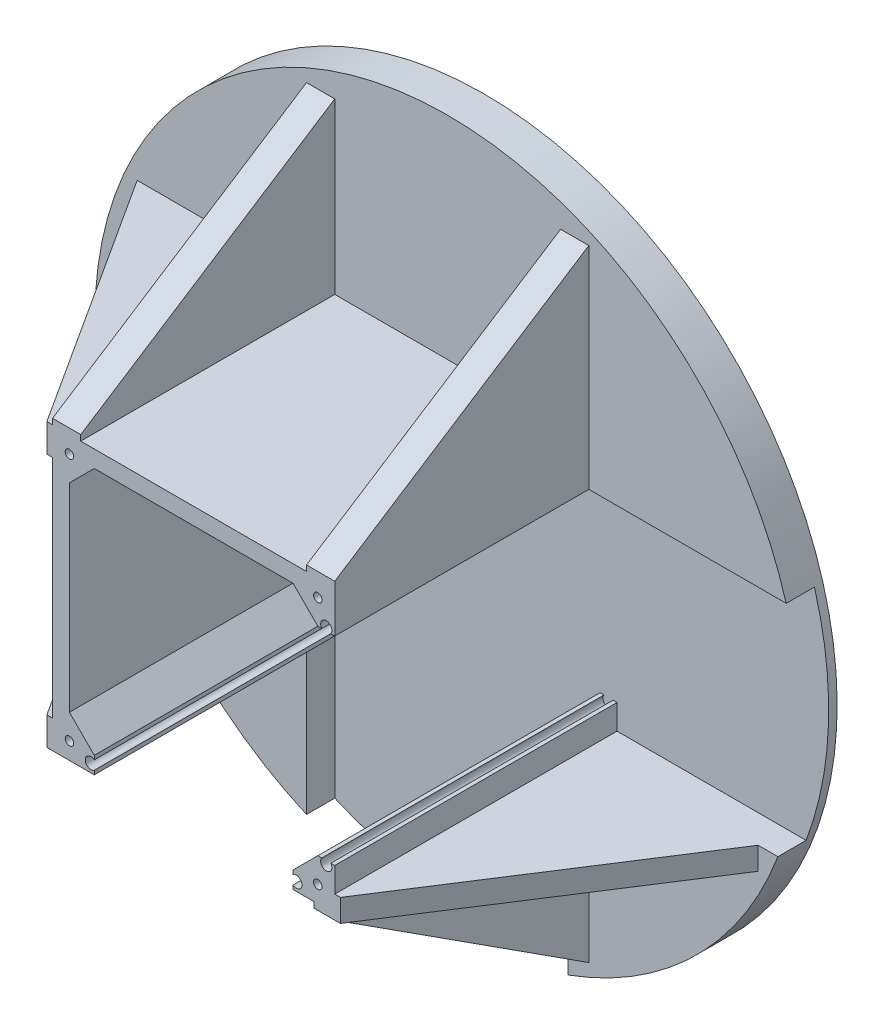
SolidWorks part; units mm, degrees
ref_plane "前视基准面" through (0, 0, 0) normal (0, 0, 1) x (1, 0, 0)
ref_plane "上视基准面" through (0, 0, 0) normal (0, 1, 0) x (1, 0, 0)
ref_plane "右视基准面" through (0, 0, 0) normal (1, 0, 0) x (0, 0, -1)
sketch "草图1" plane through (0, 0, 0) normal (0, 0, 1) x (1, 0, 0)
  line L0 (-3, -3.1574) -> (-3, -40.8426)
  line L1 (4.4, 0) -> (39.6, 0)
  line L2 (0, -4.4) -> (0, -39.6)
  line L3 (4.4, -44) -> (39.6, -44)
  line L4 (44, -4.4) -> (44, -39.6)
  line L5 (44, -44) -> (0, 0) construction
  line L6 (39.6, -44) -> (44, -39.6)
  line L7 (44, 0) -> (0, -44) construction
  line L8 (0, -4.4) -> (4.4, 0)
  line L9 (0, -22) -> (48.6163, -22) construction
  line L10 (39.6, 0) -> (44, -4.4)
  line L11 (0, -39.6) -> (4.4, -44)
  line L12 (-3, -40.8426) -> (3.1574, -47)
  line L13 (3.1574, -47) -> (40.8426, -47)
  line L14 (40.8426, -47) -> (47, -40.8426)
  line L15 (47, -3.1574) -> (47, -40.8426)
  line L16 (40.8426, 3) -> (47, -3.1574)
  line L17 (3.1574, 3) -> (40.8426, 3)
  line L18 (-3, -3.1574) -> (3.1574, 3)
  line L19 (-3, -40.8426) -> (-3, -47)
  line L20 (-3, -47) -> (3.1574, -47)
  line L21 (47, -40.8426) -> (47, -47)
  line L22 (47, -47) -> (40.8426, -47)
  dimension "D1" = 44
  dimension "D2" = 44
  dimension "D3" = 4.4
  dimension "D4" = 4.4
  dimension "D5" = 35.2
  dimension "D6" = 6.2225
  dimension "D7" = 35.2
  dimension "D8" = 35.2
  dimension "D9" = 3
extrude "凸台-拉伸2" add sketch "草图1" along normal blind 50 contours L19 L20 L12 | L18 L0 L12 L13 L14 L15 L16 L17 L11 L2 L8 L1 L10 L4 L6 L3 | L22 L21 L14
sketch "草图2" plane through (0, 0, 50) normal (0, 0, 1) x (1, 0, 0)
  line L0 (4.4, -44) -> (4.4, -47)
  line L1 (7.0436, -44) -> (7.0436, -44.7) construction
  line L2 (4.4, -44) -> (39.6, -44) construction
  line L3 (7.0436, -47) -> (7.0436, -46.3) construction
  line L4 (7.0881, -44.7) -> (4.4, -44.7) construction
  line L5 (7.0436, -46.3) -> (4.4, -46.3) construction
  line L6 (-3, -3.1574) -> (-3, -47)
  line L7 (-3, -47) -> (47, -47)
  line L8 (47, -47) -> (47, -3.1574)
  line L9 (47, -3.1574) -> (40.8426, 3)
  line L10 (40.8426, 3) -> (3.1574, 3)
  line L11 (3.1574, 3) -> (-3, -3.1574)
  line L12 (-3, -3.1574) -> (-3, -47)
  line L13 (-3, -47) -> (47, -47)
  line L14 (47, -47) -> (47, -3.1574)
  line L15 (47, -3.1574) -> (40.8426, 3)
  line L16 (40.8426, 3) -> (3.1574, 3)
  line L17 (3.1574, 3) -> (-3, -3.1574)
  line L18 (22, -47) -> (22, -44) construction
  line L19 (39.6, -44) -> (39.6, -47)
  circle A0 centre (3.8, -45.5) radius 1
  circle A1 centre (40.2, -45.5) radius 1
  line M13 (-3, -47) -> (47, -47)
  line M25 (39.6, -44) -> (4.4, -44)
  dimension "D4" = 2
  dimension "D2" = 0.7
  dimension "D3" = 0.7
  dimension "D1" = 0
extrude "切除-拉伸1" cut sketch "草图2" against normal blind 52 contours L0 A0 | L0 A0 | L19 A1 L0 A0 M25 M13 | A1 L19 | A1 L19
sketch "草图3" plane through (0, 0, 0) normal (0, 0, -1) x (-1, 0, 0)
  line L0 (0, -22) -> (-44, -22) construction
  line L1 (0, -4.4) -> (0, -39.6) construction
  line L2 (-44, -4.4) -> (-44, -39.6) construction
  line L3 (-22, 0) -> (-22, -65.109) construction
  line L4 (-4.4, 0) -> (-39.6, 0) construction
  line L5 (-4.4, -47) -> (-39.6, -47)
  line L23 (-39.6, -44) -> (-44, -39.6)
  line L24 (-39.6, -44.7) -> (-39.6, -44)
  line L25 (-39.6, -47) -> (-39.6, -46.3)
  line L26 (-47, -47) -> (-39.6, -47)
  line L27 (-47, -3.1574) -> (-47, -47)
  line L28 (-40.8426, 3) -> (-47, -3.1574)
  line L29 (-3.1574, 3) -> (-40.8426, 3)
  line L30 (3, -3.1574) -> (-3.1574, 3)
  line L31 (3, -47) -> (3, -3.1574)
  line L32 (-4.4, -47) -> (3, -47)
  line L33 (-4.4, -46.3) -> (-4.4, -47)
  line L34 (-4.4, -44) -> (-4.4, -44.7)
  line L35 (0, -39.6) -> (-4.4, -44)
  line L36 (0, -4.4) -> (0, -39.6)
  line L37 (-4.4, 0) -> (0, -4.4)
  line L38 (-39.6, 0) -> (-4.4, 0)
  line L39 (-44, -4.4) -> (-39.6, 0)
  line L40 (-44, -39.6) -> (-44, -4.4)
  line L41 (-39.6, -44) -> (-44, -39.6)
  line L42 (-39.6, -44.7) -> (-39.6, -44)
  line L43 (-39.6, -47) -> (-39.6, -46.3)
  line L44 (-47, -47) -> (-39.6, -47)
  line L45 (-47, -3.1574) -> (-47, -47)
  line L46 (-40.8426, 3) -> (-47, -3.1574)
  line L47 (-3.1574, 3) -> (-40.8426, 3)
  line L48 (3, -3.1574) -> (-3.1574, 3)
  line L49 (3, -47) -> (3, -3.1574)
  line L50 (-4.4, -47) -> (3, -47)
  line L51 (-4.4, -46.3) -> (-4.4, -47)
  line L52 (-4.4, -44) -> (-4.4, -44.7)
  line L53 (0, -39.6) -> (-4.4, -44)
  line L54 (0, -4.4) -> (0, -39.6)
  line L55 (-4.4, 0) -> (0, -4.4)
  line L56 (-39.6, 0) -> (-4.4, 0)
  line L57 (-44, -4.4) -> (-39.6, 0)
  line L58 (-44, -39.6) -> (-44, -4.4)
  circle A0 centre (-22, -22) radius 62.5
  arc A2 (-39.6, -44.7) -> (-39.6, -46.3) centre (-40.2, -45.5) ccw
  arc A3 (-4.4, -46.3) -> (-4.4, -44.7) centre (-3.8, -45.5) ccw
  arc A4 (-39.6, -44.7) -> (-39.6, -46.3) centre (-40.2, -45.5) ccw
  arc A5 (-4.4, -46.3) -> (-4.4, -44.7) centre (-3.8, -45.5) ccw
  dimension "D2" = 125
  dimension "D1" = 0
extrude "凸台-拉伸3" add sketch "草图3" along normal blind 1.5 contours A0
sketch "草图4" plane through (0, 0, 0) normal (0, 0, 1) x (1, 0, 0)
  line L1 (-3, -47) -> (-3, -79.2822)
  line L2 (47, -44) -> (80.5, -44)
  line L3 (47, -4.4) -> (81.9707, -4.4)
  line L4 (43.3, -47) -> (43.3, -80.7585)
  line L18 (44, -39.6) -> (39.6, -44)
  line L19 (39.6, -44) -> (39.6, -44.7)
  line L20 (39.6, -46.3) -> (39.6, -47)
  line L21 (39.6, -47) -> (47, -47)
  line L22 (47, -47) -> (47, -3.1574)
  line L23 (47, -3.1574) -> (40.8426, 3)
  line L24 (40.8426, 3) -> (3.1574, 3)
  line L25 (3.1574, 3) -> (-3, -3.1574)
  line L26 (-3, -3.1574) -> (-3, -47)
  line L27 (-3, -47) -> (4.4, -47)
  line L28 (4.4, -47) -> (4.4, -46.3)
  line L29 (4.4, -44.7) -> (4.4, -44)
  line L30 (4.4, -44) -> (0, -39.6)
  line L31 (0, -39.6) -> (0, -4.4)
  line L32 (0, -4.4) -> (4.4, 0)
  line L33 (4.4, 0) -> (39.6, 0)
  line L34 (39.6, 0) -> (44, -4.4)
  line L35 (44, -4.4) -> (44, -39.6)
  line L36 (44, -39.6) -> (39.6, -44)
  line L37 (39.6, -44) -> (39.6, -44.7)
  line L38 (39.6, -46.3) -> (39.6, -47)
  line L39 (39.6, -47) -> (47, -47)
  line L40 (47, -47) -> (47, -3.1574)
  line L41 (47, -3.1574) -> (40.8426, 3)
  line L42 (40.8426, 3) -> (3.1574, 3)
  line L43 (3.1574, 3) -> (-3, -3.1574)
  line L44 (-3, -3.1574) -> (-3, -47)
  line L45 (-3, -47) -> (4.4, -47)
  line L46 (4.4, -47) -> (4.4, -46.3)
  line L47 (4.4, -44.7) -> (4.4, -44)
  line L48 (4.4, -44) -> (0, -39.6)
  line L49 (0, -39.6) -> (0, -4.4)
  line L50 (0, -4.4) -> (4.4, 0)
  line L51 (4.4, 0) -> (39.6, 0)
  line L52 (39.6, 0) -> (44, -4.4)
  line L53 (44, -4.4) -> (44, -39.6)
  circle A1 centre (22, -22) radius 62.5
  circle A2 centre (22, -22) radius 62.5
  arc A4 (39.6, -46.3) -> (39.6, -44.7) centre (40.2, -45.5) ccw
  arc A5 (4.4, -44.7) -> (4.4, -46.3) centre (3.8, -45.5) ccw
  arc A6 (39.6, -46.3) -> (39.6, -44.7) centre (40.2, -45.5) ccw
  arc A7 (4.4, -44.7) -> (4.4, -46.3) centre (3.8, -45.5) ccw
  circle M22 centre (22, -22) radius 62.5
  line M35 (-3, -47) -> (-3, -3.1574)
  line M36 (-3, -3.1574) -> (3.1574, 3)
  line M37 (3.1574, 3) -> (40.8426, 3)
  line M38 (40.8426, 3) -> (47, -3.1574)
  line M39 (47, -3.1574) -> (47, -47)
  line M40 (47, -47) -> (39.6, -47)
  dimension "D1" = 0
  dimension "D2" = 0
extrude "凸台-拉伸5" add sketch "草图4" along normal blind 5 contours L3 L1 M39 M22 M35 M36 M37 M38 | L4 L2 M40 M22 M39
sketch "草图8" plane through (0, 0, 50) normal (0, 0, 1) x (1, 0, 0)
  line L0 (40.8426, 3) -> (47, 3)
  line L1 (47, 3) -> (47, -3.1574)
  line L18 (44, -39.6) -> (39.6, -44)
  line L19 (39.6, -44) -> (39.6, -44.7)
  line L20 (39.6, -46.3) -> (39.6, -47)
  line L21 (39.6, -47) -> (47, -47)
  line L22 (47, -47) -> (47, -3.1574)
  line L23 (47, -3.1574) -> (40.8426, 3)
  line L24 (40.8426, 3) -> (3.1574, 3)
  line L25 (3.1574, 3) -> (-3, -3.1574)
  line L26 (-3, -3.1574) -> (-3, -47)
  line L27 (-3, -47) -> (4.4, -47)
  line L28 (4.4, -47) -> (4.4, -46.3)
  line L29 (4.4, -44.7) -> (4.4, -44)
  line L30 (4.4, -44) -> (0, -39.6)
  line L31 (0, -39.6) -> (0, -4.4)
  line L32 (0, -4.4) -> (4.4, 0)
  line L33 (4.4, 0) -> (39.6, 0)
  line L34 (39.6, 0) -> (44, -4.4)
  line L35 (44, -4.4) -> (44, -39.6)
  line L36 (44, -39.6) -> (39.6, -44)
  line L37 (39.6, -44) -> (39.6, -44.7)
  line L38 (39.6, -46.3) -> (39.6, -47)
  line L39 (39.6, -47) -> (47, -47)
  line L40 (47, -47) -> (47, -3.1574)
  line L41 (47, -3.1574) -> (40.8426, 3)
  line L42 (40.8426, 3) -> (3.1574, 3)
  line L43 (3.1574, 3) -> (-3, -3.1574)
  line L44 (-3, -3.1574) -> (-3, -47)
  line L45 (-3, -47) -> (4.4, -47)
  line L46 (4.4, -47) -> (4.4, -46.3)
  line L47 (4.4, -44.7) -> (4.4, -44)
  line L48 (4.4, -44) -> (0, -39.6)
  line L49 (0, -39.6) -> (0, -4.4)
  line L50 (0, -4.4) -> (4.4, 0)
  line L51 (4.4, 0) -> (39.6, 0)
  line L52 (39.6, 0) -> (44, -4.4)
  line L53 (44, -4.4) -> (44, -39.6)
  arc A2 (39.6, -46.3) -> (39.6, -44.7) centre (40.2, -45.5) ccw
  arc A3 (4.4, -44.7) -> (4.4, -46.3) centre (3.8, -45.5) ccw
  arc A4 (39.6, -46.3) -> (39.6, -44.7) centre (40.2, -45.5) ccw
  arc A5 (4.4, -44.7) -> (4.4, -46.3) centre (3.8, -45.5) ccw
  line M27 (47, -3.1574) -> (40.8426, 3)
  dimension "D1" = 0
extrude "凸台-拉伸6" add sketch "草图8" against normal blind 47 contours L1 L0 M27
sketch "草图9" plane through (0, 0, 50) normal (0, 0, 1) x (1, 0, 0)
  line L0 (44, -38.5401) -> (44.7, -38.5401) construction
  line L1 (47, -38.5401) -> (46.3, -38.5401) construction
  line L2 (44, -39.6) -> (47, -39.6)
  line L3 (44.7, -38.5401) -> (44.7, -39.6) construction
  line L4 (46.3, -38.5401) -> (46.3, -39.6) construction
  line L5 (47, -22) -> (44, -22) construction
  line L6 (44, -4.4) -> (47, -4.4)
  line L17 (44, -39.6) -> (39.6, -44)
  line L18 (39.6, -44) -> (39.6, -44.7)
  line L19 (39.6, -46.3) -> (39.6, -47)
  line L20 (39.6, -47) -> (47, -47)
  line L21 (47, -47) -> (47, 3)
  line L22 (47, 3) -> (3.1574, 3)
  line L23 (3.1574, 3) -> (-3, -3.1574)
  line L24 (-3, -3.1574) -> (-3, -47)
  line L25 (-3, -47) -> (4.4, -47)
  line L26 (4.4, -47) -> (4.4, -46.3)
  line L27 (4.4, -44.7) -> (4.4, -44)
  line L28 (4.4, -44) -> (0, -39.6)
  line L29 (0, -39.6) -> (0, -4.4)
  line L30 (0, -4.4) -> (4.4, 0)
  line L31 (4.4, 0) -> (39.6, 0)
  line L32 (39.6, 0) -> (44, -4.4)
  line L33 (44, -4.4) -> (44, -39.6)
  line L34 (44, -39.6) -> (39.6, -44)
  line L35 (39.6, -44) -> (39.6, -44.7)
  line L36 (39.6, -46.3) -> (39.6, -47)
  line L37 (39.6, -47) -> (47, -47)
  line L38 (47, -47) -> (47, 3)
  line L39 (47, 3) -> (3.1574, 3)
  line L40 (3.1574, 3) -> (-3, -3.1574)
  line L41 (-3, -3.1574) -> (-3, -47)
  line L42 (-3, -47) -> (4.4, -47)
  line L43 (4.4, -47) -> (4.4, -46.3)
  line L44 (4.4, -44.7) -> (4.4, -44)
  line L45 (4.4, -44) -> (0, -39.6)
  line L46 (0, -39.6) -> (0, -4.4)
  line L47 (0, -4.4) -> (4.4, 0)
  line L48 (4.4, 0) -> (39.6, 0)
  line L49 (39.6, 0) -> (44, -4.4)
  line L50 (44, -4.4) -> (44, -39.6)
  circle A0 centre (45.5, -40.2) radius 1
  circle A1 centre (45.5, -3.8) radius 1
  arc A2 (39.6, -46.3) -> (39.6, -44.7) centre (40.2, -45.5) ccw
  arc A3 (4.4, -44.7) -> (4.4, -46.3) centre (3.8, -45.5) ccw
  arc A4 (39.6, -46.3) -> (39.6, -44.7) centre (40.2, -45.5) ccw
  arc A5 (4.4, -44.7) -> (4.4, -46.3) centre (3.8, -45.5) ccw
  line M30 (47, -47) -> (47, 3)
  line M43 (44, -4.4) -> (44, -39.6)
  dimension "D4" = 2
  dimension "D2" = 0.7
  dimension "D3" = 0.7
  dimension "D1" = 0
extrude "切除-拉伸2" cut sketch "草图9" against normal up to surface (50 mm away) contours L6 A1 L2 A0 M43 M30 | A1 L6 | A1 L6 | L2 A0 | L2 A0 up to face at (64.9231, -24.2299, 0)
sketch "草图11" plane through (0, 0, 50) normal (0, 0, 1) x (1, 0, 0)
  line L0 (-3, -3.1574) -> (-3, 3)
  line L1 (-3, 3) -> (3.1574, 3)
  line L14 (46.3, -4.4) -> (47, -4.4)
  line L15 (47, -4.4) -> (47, 3)
  line L16 (47, 3) -> (3.1574, 3)
  line L17 (3.1574, 3) -> (-3, -3.1574)
  line L18 (-3, -3.1574) -> (-3, -47)
  line L19 (-3, -47) -> (4.4, -47)
  line L20 (4.4, -47) -> (4.4, -46.3)
  line L21 (4.4, -44.7) -> (4.4, -44)
  line L22 (4.4, -44) -> (0, -39.6)
  line L23 (0, -39.6) -> (0, -4.4)
  line L24 (0, -4.4) -> (4.4, 0)
  line L25 (4.4, 0) -> (39.6, 0)
  line L26 (39.6, 0) -> (44, -4.4)
  line L27 (44, -4.4) -> (44.7, -4.4)
  line L28 (46.3, -4.4) -> (47, -4.4)
  line L29 (47, -4.4) -> (47, 3)
  line L30 (47, 3) -> (3.1574, 3)
  line L31 (3.1574, 3) -> (-3, -3.1574)
  line L32 (-3, -3.1574) -> (-3, -47)
  line L33 (-3, -47) -> (4.4, -47)
  line L34 (4.4, -47) -> (4.4, -46.3)
  line L35 (4.4, -44.7) -> (4.4, -44)
  line L36 (4.4, -44) -> (0, -39.6)
  line L37 (0, -39.6) -> (0, -4.4)
  line L38 (0, -4.4) -> (4.4, 0)
  line L39 (4.4, 0) -> (39.6, 0)
  line L40 (39.6, 0) -> (44, -4.4)
  line L41 (44, -4.4) -> (44.7, -4.4)
  arc A2 (46.3, -4.4) -> (44.7, -4.4) centre (45.5, -3.8) ccw
  arc A3 (4.4, -44.7) -> (4.4, -46.3) centre (3.8, -45.5) ccw
  arc A4 (46.3, -4.4) -> (44.7, -4.4) centre (45.5, -3.8) ccw
  arc A5 (4.4, -44.7) -> (4.4, -46.3) centre (3.8, -45.5) ccw
  line M21 (3.1574, 3) -> (-3, -3.1574)
  dimension "D1" = 0
extrude "凸台-拉伸7" add sketch "草图11" against normal through all contours L1 L0 M21
sketch "草图12" plane through (0, 0, 50) normal (0, 0, 1) x (1, 0, 0)
  line L0 (0, -4.4) -> (0, 0) construction
  line L1 (0, 0) -> (4.4, 0) construction
  line L2 (39.6, 0) -> (44, 0) construction
  line L3 (44, 0) -> (44, -4.4) construction
  line L4 (-3, -22) -> (61.1662, -22) construction
  line L7 (47, -39.6) -> (46.3, -39.6)
  line L8 (44.7, -39.6) -> (44, -39.6)
  line L9 (44, -39.6) -> (39.6, -44)
  line L10 (39.6, -44) -> (39.6, -44.7)
  line L11 (39.6, -46.3) -> (39.6, -47)
  line L12 (39.6, -47) -> (47, -47)
  line L13 (46.3, -4.4) -> (47, -4.4)
  line L14 (47, -4.4) -> (47, 3)
  line L15 (47, 3) -> (-3, 3)
  line L16 (-3, 3) -> (-3, -47)
  line L17 (-3, -47) -> (4.4, -47)
  line L18 (4.4, -47) -> (4.4, -46.3)
  line L19 (4.4, -44.7) -> (4.4, -44)
  line L20 (4.4, -44) -> (0, -39.6)
  line L21 (0, -39.6) -> (0, -4.4)
  line L22 (0, -4.4) -> (4.4, 0)
  line L23 (4.4, 0) -> (39.6, 0)
  line L24 (39.6, 0) -> (44, -4.4)
  line L25 (44, -4.4) -> (44.7, -4.4)
  line L26 (46.3, -4.4) -> (47, -4.4)
  line L27 (47, -4.4) -> (47, 3)
  line L28 (47, 3) -> (-3, 3)
  line L29 (-3, 3) -> (-3, -47)
  line L30 (-3, -47) -> (4.4, -47)
  line L31 (4.4, -47) -> (4.4, -46.3)
  line L32 (4.4, -44.7) -> (4.4, -44)
  line L33 (4.4, -44) -> (0, -39.6)
  line L34 (0, -39.6) -> (0, -4.4)
  line L35 (0, -4.4) -> (4.4, 0)
  line L36 (4.4, 0) -> (39.6, 0)
  line L37 (39.6, 0) -> (44, -4.4)
  line L38 (44, -4.4) -> (44.7, -4.4)
  line L39 (47, -47) -> (47, -39.6)
  line L40 (47, -39.6) -> (46.3, -39.6)
  line L41 (44.7, -39.6) -> (44, -39.6)
  line L42 (44, -39.6) -> (39.6, -44)
  line L43 (39.6, -44) -> (39.6, -44.7)
  line L44 (39.6, -46.3) -> (39.6, -47)
  line L45 (39.6, -47) -> (47, -47)
  line L46 (47, -47) -> (47, -39.6)
  circle A0 centre (0, 0) radius 0.75
  circle A1 centre (44, 0) radius 0.75
  arc A2 (46.3, -4.4) -> (44.7, -4.4) centre (45.5, -3.8) ccw
  arc A3 (4.4, -44.7) -> (4.4, -46.3) centre (3.8, -45.5) ccw
  arc A4 (46.3, -4.4) -> (44.7, -4.4) centre (45.5, -3.8) ccw
  arc A5 (4.4, -44.7) -> (4.4, -46.3) centre (3.8, -45.5) ccw
  arc A6 (44.7, -39.6) -> (46.3, -39.6) centre (45.5, -40.2) ccw
  arc A7 (39.6, -46.3) -> (39.6, -44.7) centre (40.2, -45.5) ccw
  arc A8 (44.7, -39.6) -> (46.3, -39.6) centre (45.5, -40.2) ccw
  arc A9 (39.6, -46.3) -> (39.6, -44.7) centre (40.2, -45.5) ccw
  circle A10 centre (0, -44) radius 0.75
  circle A11 centre (44, -44) radius 0.75
  dimension "D3" = 1.5
  dimension "D4" = 1.5
  dimension "D1" = 0
  dimension "D2" = 0
extrude "切除-拉伸3" cut sketch "草图12" against normal blind 5 contours A0 | A1 | A11 | A10
sketch "草图13" plane through (0, 0, 5) normal (0, 0, 1) x (1, 0, 0)
  line L0 (43.3, -47) -> (43.3, -80.7585) construction
  line L1 (47, -47) -> (43.3, -47)
  line L2 (47, -47) -> (47, -77)
  line L3 (47, -77) -> (43.3, -77)
  line L4 (43.3, -47) -> (43.3, -77)
  dimension "D1" = 30
sketch "草图14" plane through (0, 0, 50) normal (0, 0, 1) x (1, 0, 0)
  line L0 (47, -47) -> (47, -77) construction
  line L1 (43.3, -47) -> (47, -47)
  line L2 (43.3, -47) -> (43.3, -48)
  line L3 (43.3, -48) -> (47, -48)
  line L4 (47, -47) -> (47, -48)
  dimension "D1" = 1
loft "放样3" add profiles "草图14", "草图13"
sketch "草图15" plane through (0, 0, 5) normal (0, 0, 1) x (1, 0, 0)
  line L0 (47, -44) -> (47, -77) construction
  line L1 (47, -44) -> (77, -44)
  line L2 (47, -44) -> (47, -48)
  line L3 (47, -48) -> (77, -48)
  line L4 (77, -44) -> (77, -48)
  line L5 (47, -39.6) -> (47, -47) construction
  line L6 (43.3, -48) -> (47, -48) construction
  dimension "D1" = 30
  dimension "D2" = 4
  dimension "D3" = 4
sketch "草图16" plane through (0, 0, 50) normal (0, 0, 1) x (1, 0, 0)
  line L0 (47, -48) -> (77, -48) construction
  line L1 (47, -44) -> (47, -48) construction
  line L2 (47, -44) -> (77, -44) construction
  line L3 (47, -48) -> (48, -48)
  line L4 (47, -48) -> (47, -44)
  line L5 (47, -44) -> (48, -44)
  line L6 (48, -48) -> (48, -44)
  point P0 (48, -48)
  dimension "D1" = 1
loft "放样4" add profiles "草图15", "草图16"
sketch "草图17" plane through (0, 0, 5) normal (0, 0, 1) x (1, 0, 0)
  line L1 (-3, 3) -> (-33, 3)
  line L2 (-3, 3) -> (-3, -2)
  line L3 (-3, -2) -> (-33, -2)
  line L4 (-33, 3) -> (-33, -2)
  dimension "D1" = 30
  dimension "D2" = 5
sketch "草图18" plane through (0, 0, 50) normal (0, 0, 1) x (1, 0, 0)
  line L0 (-3, -2) -> (-33, -2) construction
  line L1 (-3, 3) -> (-4, 3)
  line L2 (-3, 3) -> (-3, -2)
  line L3 (-3, -2) -> (-4, -2)
  line L4 (-4, 3) -> (-4, -2)
  dimension "D1" = 1
loft "放样5" add profiles "草图18", "草图17"
sketch "草图19" plane through (0, 0, 5) normal (0, 0, 1) x (1, 0, 0)
  line L1 (47, 3) -> (42, 3)
  line L2 (47, 3) -> (47, 33)
  line L3 (47, 33) -> (42, 33)
  line L4 (42, 3) -> (42, 33)
  dimension "D1" = 5
  dimension "D2" = 30
sketch "草图20" plane through (0, 0, 50) normal (0, 0, 1) x (1, 0, 0)
  line L0 (47, 3) -> (47, 33) construction
  line L1 (42, 3) -> (47, 3)
  line L2 (42, 3) -> (42, 4)
  line L3 (42, 4) -> (47, 4)
  line L4 (47, 3) -> (47, 4)
  dimension "D1" = 1
loft "放样6" add profiles "草图20", "草图19"
sketch "草图21" plane through (0, 0, 5) normal (0, 0, 1) x (1, 0, 0)
  line L1 (-3, -47) -> (-33, -47)
  line L2 (-3, -47) -> (-3, -42)
  line L3 (-3, -42) -> (-33, -42)
  line L4 (-33, -47) -> (-33, -42)
  dimension "D1" = 5
  dimension "D2" = 30
sketch "草图22" plane through (0, 0, 50) normal (0, 0, 1) x (1, 0, 0)
  line L0 (-3, -42) -> (-33, -42) construction
  line L1 (-3, -47) -> (-4, -47)
  line L2 (-3, -47) -> (-3, -42)
  line L3 (-3, -42) -> (-4, -42)
  line L4 (-4, -47) -> (-4, -42)
  dimension "D1" = 1
loft "放样7" add profiles "草图22", "草图21"
sketch "草图23" plane through (0, 0, 5) normal (0, 0, 1) x (1, 0, 0)
  line L0 (-3, -2) -> (-3, 3) construction
  line L1 (-33, 3) -> (42, 3) construction
  line L2 (-3, 3) -> (42, 3) construction
  line L4 (-3, 3) -> (2, 3)
  line L5 (-3, 3) -> (-3, 33)
  line L6 (-3, 33) -> (2, 33)
  line L7 (2, 3) -> (2, 33)
  dimension "D1" = 5
  dimension "D2" = 30
sketch "草图24" plane through (0, 0, 50) normal (0, 0, 1) x (1, 0, 0)
  line L0 (2, 3) -> (2, 33) construction
  line L1 (-3, 3) -> (2, 3)
  line L2 (-3, 3) -> (-3, 4)
  line L3 (-3, 4) -> (2, 4)
  line L4 (2, 3) -> (2, 4)
  dimension "D1" = 1
loft "放样9" add profiles "草图24", "草图23"
